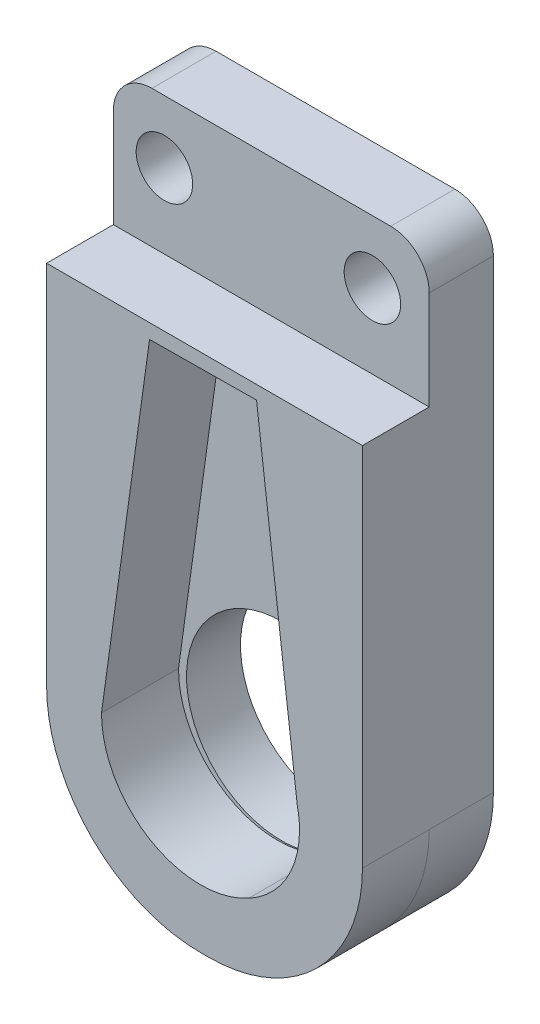
SolidWorks part; units mm, degrees
ref_plane "Front Plane" through (0, 0, 0) normal (0, 0, 1) x (1, 0, 0)
ref_plane "Top Plane" through (0, 0, 0) normal (0, 1, 0) x (1, 0, 0)
ref_plane "Right Plane" through (0, 0, 0) normal (1, 0, 0) x (0, 0, -1)
other "Graphic1"
ref_plane "Plane2" through (0, 0, 10) normal (0, 0, 1) x (1, 0, 0)
sketch "Sketch2" plane through (0, 0, 10) normal (0, 0, 1) x (1, 0, 0)
  line L1 (-326.0372, 240.3637) -> (-313.7372, 240.3637)
  line L2 (-326.0372, 240.3637) -> (-326.0372, 214.7637)
  line L3 (-326.0372, 214.7637) -> (-313.7372, 214.7637)
  line L4 (-313.7372, 240.3637) -> (-313.7372, 214.7637)
  dimension "D1" = 12.3
  dimension "D2" = 25.6
extrude "Boss-Extrude1" add sketch "Sketch2" along normal blind 2.5
fillet "Fillet1" radius 6 2 edges at (-313.7372, 214.7637, 11.25) (-326.0372, 214.7637, 11.25)
fillet "Fillet2" radius 1.5 2 edges at (-326.0372, 240.3637, 11.25) (-313.7372, 240.3637, 11.25)
sketch "Sketch3" plane through (0, 0, 12.5) normal (0, 0, 1) x (1, 0, 0)
  circle A0 centre (-324.0491, 237.9223) radius 1.1
  circle A1 centre (-315.9491, 237.9223) radius 1.1
  dimension "D1" = 2.2
  dimension "D2" = 2.2
  dimension "D3" = 8.1
extrude "Cut-Extrude1" cut sketch "Sketch3" against normal blind 3.5
ref_plane "Plane3" through (0, 0, 12.5) normal (0, 0, 1) x (1, 0, 0)
sketch "Sketch4" plane through (0, 0, 12.5) normal (0, 0, 1) x (1, 0, 0)
  line L0 (-326.0372, 238.8637) -> (-326.0372, 220.7637) construction
  line L1 (-326.0372, 235.0154) -> (-313.7372, 235.0154)
  line L2 (-326.0372, 235.0154) -> (-326.0372, 214.7637)
  line L3 (-326.0372, 214.7637) -> (-313.7372, 214.7637)
  line L4 (-313.7372, 235.0154) -> (-313.7372, 214.7637)
extrude "Boss-Extrude2" add sketch "Sketch4" along normal blind 2.6
fillet "Fillet3" radius 6 2 edges at (-313.7372, 214.7637, 13.8) (-326.0372, 214.7637, 13.8)
sketch "Sketch5" plane through (0, 0, 15.1) normal (0, 0, 1) x (1, 0, 0)
  line L0 (-319.8872, 235.0154) -> (-319.8872, 211.9352) construction
  line L1 (-313.7372, 235.0154) -> (-326.0372, 235.0154) construction
  circle A0 centre (-319.8872, 220.8121) radius 3.7
  dimension "D1" = 7.4
extrude "Cut-Extrude2" cut sketch "Sketch5" against normal through all
sketch "Sketch6" plane through (0, 0, 15.1) normal (0, 0, 1) x (1, 0, 0)
  line L0 (-322.0282, 234.4487) -> (-317.8616, 234.486)
  line L1 (-317.8616, 234.486) -> (-316.1885, 220.9106)
  line L2 (-322.0282, 234.4487) -> (-323.899, 220.9175)
  circle A0 centre (-319.8872, 220.8121) radius 3.7 construction
  arc A1 (-323.899, 220.9175) -> (-316.1885, 220.9106) centre (-320.0438, 220.9035) ccw
extrude "Cut-Extrude3" cut sketch "Sketch6" against normal blind 3
